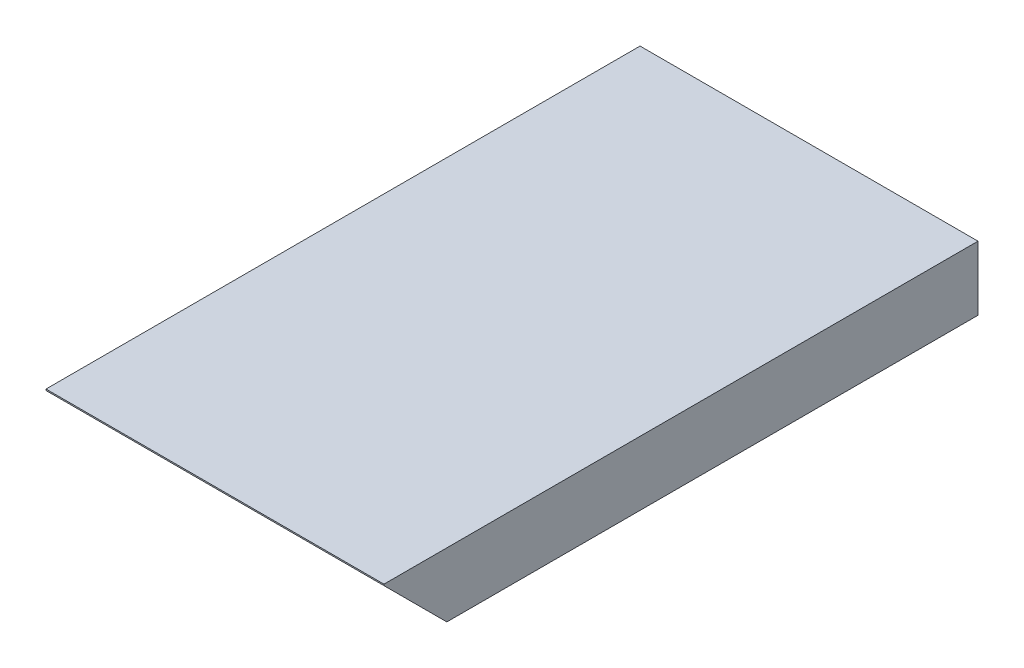
SolidWorks part; units mm, degrees
material "Verre"
ref_plane "Plan de face" through (0, 0, 0) normal (0, 0, 1) x (1, 0, 0)
ref_plane "Plan de dessus" through (0, 0, 0) normal (0, 1, 0) x (1, 0, 0)
ref_plane "Plan de droite" through (0, 0, 0) normal (1, 0, 0) x (0, 0, -1)
sketch "Esquisse1" plane through (0, 0, 0) normal (0, 1, 0) x (1, 0, 0)
  line L1 (-12.9, 24) -> (12.9, 24)
  line L2 (-12.9, 24) -> (-12.9, -21.3492)
  line L3 (-12.9, -21.3492) -> (12.9, -21.3492)
  line L4 (12.9, 24) -> (12.9, -21.3492)
  line L5 (12.9, -14.8492) -> (12.9, 26.0707) construction
  line L7 (-12.9, -14.8492) -> (-12.9, 26.0707) construction
  line L9 (12.9, -14.8492) -> (-12.9, -14.8492) construction
  point P10 (0, -14.8492)
  dimension "D1" = 24
  dimension "D2" = 6.5
  dimension "D3" = 25.8
extrude "Extrusion1" add sketch "Esquisse1" along normal blind 4.9
chamfer "Chanfrein2" distance 4.8 angle 45 1 edges at (0, 0, 21.3492)
